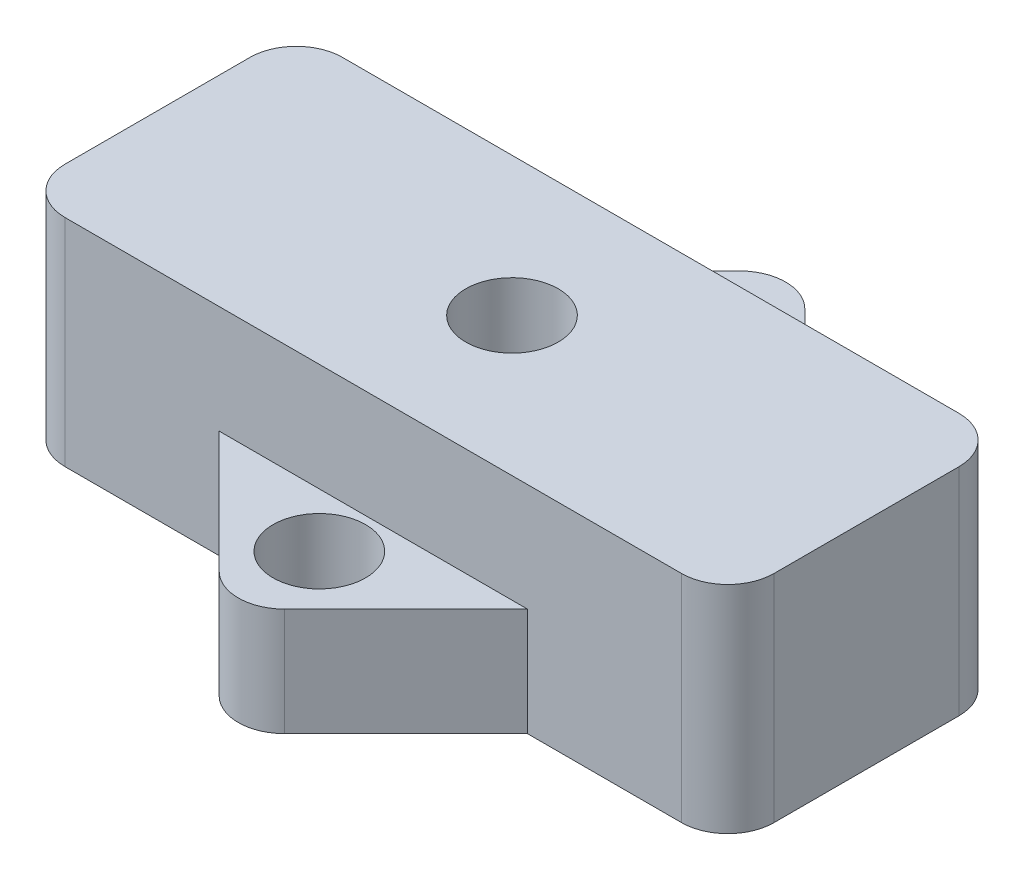
SolidWorks part; units mm, degrees
ref_plane "Front Plane" through (0, 0, 0) normal (0, 0, 1) x (1, 0, 0)
ref_plane "Top Plane" through (0, 0, 0) normal (0, 1, 0) x (1, 0, 0)
ref_plane "Right Plane" through (0, 0, 0) normal (1, 0, 0) x (0, 0, -1)
sketch "Sketch1" plane through (0, 0, 0) normal (0, 1, 0) x (1, 0, 0)
  line L1 (-20, -9) -> (20, -9)
  line L2 (-23, -6) -> (-23, 6)
  line L3 (-20, 9) -> (20, 9)
  line L4 (23, -6) -> (23, 6)
  line L5 (-23, -9) -> (23, 9) construction
  line L6 (-23, 9) -> (23, -9) construction
  arc A0 (20, 9) -> (23, 6) centre (20, 6) cw
  arc A1 (20, -9) -> (23, -6) centre (20, -6) ccw
  arc A2 (-20, -9) -> (-23, -6) centre (-20, -6) cw
  arc A3 (-23, 6) -> (-20, 9) centre (-20, 6) cw
  point P0 (0, 0)
  dimension "D1" = 3
extrude "box" add sketch "Sketch1" along normal blind 14
sketch "Sketch3" plane through (0, 0, 0) normal (0, -1, 0) x (1, 0, 0)
  line L0 (-10, -9) -> (-2.1213, -16.8787)
  line L1 (20, -9) -> (-20, -9) construction
  line L2 (2.1213, -16.8787) -> (10, -9)
  line L3 (-23, 0) -> (23, 0) construction
  line L4 (-23, -6) -> (-23, 6) construction
  line L5 (23, 6) -> (23, -6) construction
  line L6 (2.1213, 16.8787) -> (10, 9)
  line L7 (-10, 9) -> (-2.1213, 16.8787)
  line L8 (-10, -9) -> (10, -9)
  line L9 (-10, 9) -> (10, 9)
  arc A0 (2.1213, 16.8787) -> (-2.1213, 16.8787) centre (0, 14.7574) ccw
  arc A1 (-2.1213, -16.8787) -> (2.1213, -16.8787) centre (0, -14.7574) ccw
  point P17 (0, 19)
  point P20 (0, -19)
  dimension "D2" = 3
  dimension "D1" = 10
extrude "triangle" add sketch "Sketch3" against normal blind 7
sketch "Sketch4" plane through (0, 0, 0) normal (0, -1, 0) x (1, 0, 0)
  line L1 (0, 15.5) -> (0, 12.5) construction
  line L2 (0, -15.5) -> (0, -12.5) construction
  line L3 (0, 15.5) -> (0, -15.5) construction
  circle A0 centre (0, 12.5) radius 3
  circle A1 centre (0, 0) radius 3
  circle A2 centre (0, -12.5) radius 3
  point P4 (0, 0)
extrude "Cut-Extrude1" cut sketch "Sketch4" against normal through all
